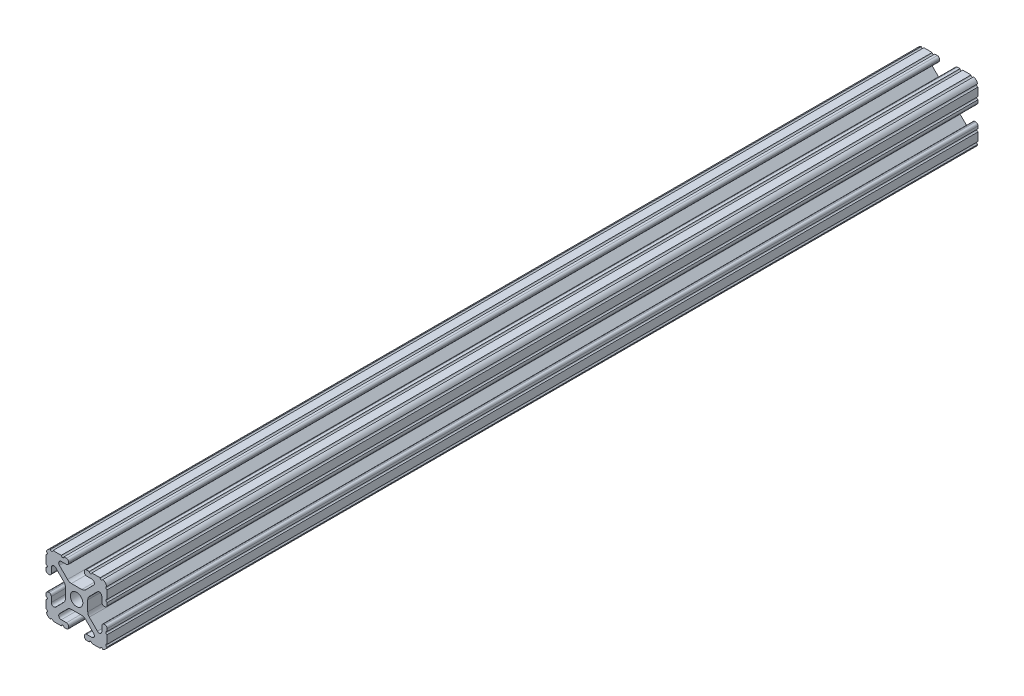
SolidWorks part; units mm, degrees
ref_plane "Front Plane" through (0, 0, 0) normal (0, 0, 1) x (1, 0, 0)
ref_plane "Top Plane" through (0, 0, 0) normal (0, 1, 0) x (1, 0, 0)
ref_plane "Right Plane" through (0, 0, 0) normal (1, 0, 0) x (0, 0, -1)
sketch "Sketch2" plane through (0, 0, 0) normal (0, 0, 1) x (1, 0, 0)
  line L0 (0, 12.7) -> (0, -12.7) construction
  line L1 (-12.7, 0) -> (12.7, 0) construction
  line L2 (3.2512, -12.7) -> (12.7, -12.7)
  line L3 (12.7, -12.7) -> (12.7, -3.2512)
  line L4 (3.2512, -12.7) -> (3.2512, -10.4902)
  line L5 (3.2512, -10.4902) -> (8.9276, -10.4902)
  line L6 (8.9276, -10.4902) -> (3.0856, -4.6482)
  line L7 (0, 0) -> (12.7, -12.7) construction
  line L8 (12.7, -3.2512) -> (10.4902, -3.2512)
  line L9 (10.4902, -3.2512) -> (10.4902, -8.9276)
  line L10 (10.4902, -8.9276) -> (4.6482, -3.0856)
  circle A0 centre (0, 0) radius 2.6035
  arc A1 (6.3485, -10.4902) -> (7.1039, -8.6665) centre (6.3485, -9.4219) ccw construction
  point P8 (0, -4.6482)
  dimension "Center Hole Diameter" = 5.207
  dimension "Rail Height" = 25.4
  dimension "Rail Width" = 25.4
  dimension "T-Slot Width" = 6.5024
  dimension "Slot Inner Width" = 14.8336
  dimension "Thickness" = 2.2098
  dimension "Slot Depth" = 5.842
  dimension "D1" = 2.2098
sketch "Sketch3" plane through (0, 0, 0) normal (1, 0, 0) x (0, 0, -1)
  line L0 (-1524, -12.7) -> (1524, -12.7) construction
  line L1 (-1498.6, 0) -> (1498.6, 0) construction
  dimension "Length" = 3048
  dimension "D1" = 25.4
sketch "Sketch4" plane through (0, 0, 0) normal (0, 0, 1) x (1, 0, 0)
  line L0 (4.1904, -12.7) -> (10.1173, -12.7)
  line L1 (3.2512, -12.7) -> (12.7, -12.7) construction
  line L2 (3.2512, -12.7) -> (3.2512, -10.4902) construction
  line L3 (3.2512, -10.4902) -> (8.9276, -10.4902) construction
  line L4 (3.2512, -11.4294) -> (3.2512, -11.7608)
  line L5 (4.1904, -10.4902) -> (6.3485, -10.4902)
  line L6 (0, -4.6482) -> (2.164, -4.6482)
  line L7 (8.9276, -10.4902) -> (3.0856, -4.6482) construction
  line L8 (3.7373, -5.2999) -> (7.1039, -8.6665)
  line L9 (12.7, -12.7) -> (12.7, -3.2512) construction
  line L10 (10.4902, -8.9276) -> (4.6482, -3.0856) construction
  line L11 (10.4902, -3.2512) -> (10.4902, -8.9276) construction
  line L12 (10.4902, -6.3485) -> (10.4902, -4.1904)
  line L13 (12.7, -3.2512) -> (10.4902, -3.2512) construction
  line L14 (11.4294, -3.2512) -> (11.7608, -3.2512)
  line L15 (12.7, -4.1904) -> (12.7, -10.1173)
  line L16 (8.6665, -7.1039) -> (5.2999, -3.7373)
  line L17 (4.6482, 0) -> (4.6482, -2.164)
  line L18 (-12.7, 0) -> (12.7, 0) construction
  line L19 (0, -4.6482) -> (0, -2.6035)
  line L20 (0, 12.7) -> (0, -12.7) construction
  line L21 (4.6482, 0) -> (2.6035, 0)
  arc A0 (3.2512, -11.7608) -> (4.1904, -12.7) centre (4.1904, -11.7608) ccw
  arc A2 (3.2512, -11.4294) -> (4.1904, -10.4902) centre (4.1904, -11.4294) cw
  arc A3 (6.3485, -10.4902) -> (7.1039, -8.6665) centre (6.3485, -9.4219) ccw
  arc A4 (2.164, -4.6482) -> (3.7373, -5.2999) centre (2.164, -6.8732) cw
  arc A5 (10.1173, -12.7) -> (12.7, -10.1173) centre (10.1173, -10.1173) ccw
  arc A6 (8.6665, -7.1039) -> (10.4902, -6.3485) centre (9.4219, -6.3485) ccw
  arc A7 (10.4902, -4.1904) -> (11.4294, -3.2512) centre (11.4294, -4.1904) cw
  arc A8 (11.7608, -3.2512) -> (12.7, -4.1904) centre (11.7608, -4.1904) cw
  arc A9 (5.2999, -3.7373) -> (4.6482, -2.164) centre (6.8732, -2.164) cw
  circle A10 centre (0, 0) radius 2.6035 construction
  arc A11 (0, -2.6035) -> (2.6035, 0) centre (0, 0) ccw
  dimension "D1" = 2.5827
  dimension "D2" = 2.225
  dimension "D3" = 0.9392
extrude "Boss-Extrude1" add sketch "Sketch4" along normal mid plane 3048
sketch "Sketch5" plane through (0, 0, 0) normal (0, 0, 1) x (1, 0, 0)
  line L0 (3.2512, -12.7) -> (12.7, -12.7) construction
  line L1 (4.1904, -10.4902) -> (6.3485, -10.4902) construction
  line L3 (0, 0) -> (12.7, -12.7) construction
  line L4 (6.3485, -10.4902) -> (6.3485, -12.7) construction
  line L5 (8.9276, -10.4902) -> (3.0856, -4.6482) construction
  circle A0 centre (10.3562, -12.7) radius 0.5524
  circle A1 centre (5.796, -12.7) radius 0.5524
  circle A2 centre (12.7, -10.3562) radius 0.5524
  circle A3 centre (12.7, -5.796) radius 0.5524
  point P10 (5.2694, -10.4902)
  point P12 (9.4219, -6.3485)
  dimension "D1" = 1.1049
extrude "Cut-Extrude1" cut sketch "Sketch5" against normal through all both and the other way through all
mirror "Mirror1" about plane through (0, 0, 0) normal (1, 0, 0) of bodies 137 134
mirror "Mirror2" about plane through (0, 0, 0) normal (0, 1, 0) of bodies 135
sketch "Sketch8" plane through (0, 0, 0) normal (0, 1, 0) x (1, 0, 0)
  line L0 (-12.58, 1524) -> (-12.58, -1524) construction
  line L1 (-25.28, 1536.7) -> (25.28, 1536.7)
  line L2 (-25.28, 1536.7) -> (-25.28, -1162.05)
  line L3 (-25.28, -1162.05) -> (25.28, -1162.05)
  line L4 (25.28, 1536.7) -> (25.28, -1162.05)
  line L5 (12.58, 1524) -> (12.58, -1524) construction
  line L7 (-6.3485, -1524) -> (-9.8037, -1524) construction
  dimension "D1" = 12.7
  dimension "D2" = 12.7
  dimension "D3" = 12.7
  dimension "D4" = 361.95
extrude "Cut-Extrude2" cut sketch "Sketch8" against normal through all both and the other way through all
equation "\"D1@Boss-Extrude1\"=\"Length@Sketch3\""
equation "\"D1@Sketch2\"=\"Thickness@Sketch2\""
equation "\"D2@Sketch4\"=\"Slot Inner Width@Sketch2\"*0.15"
equation "\"D1@Sketch4\"=\"D3@Sketch4\"*2.75"
equation "\"D3@Sketch4\"=\"Thickness@Sketch2\"*0.425"
equation "\"D1@Sketch5\"=\"Thickness@Sketch2\"*0.5"
